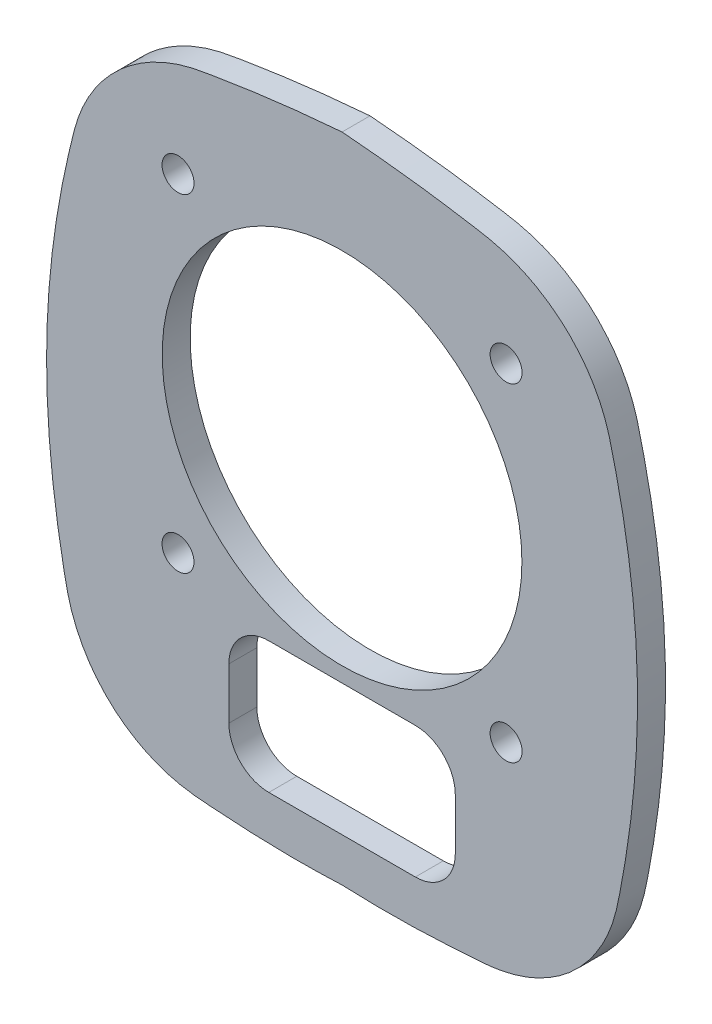
SolidWorks part; units mm, degrees
material "Фанера"
ref_plane "Front Plane" through (0, 0, 0) normal (0, 0, 1) x (1, 0, 0)
ref_plane "Top Plane" through (0, 0, 0) normal (0, 1, 0) x (1, 0, 0)
ref_plane "Right Plane" through (0, 0, 0) normal (1, 0, 0) x (0, 0, -1)
sketch "Эскиз1" plane through (0, 0, 0) normal (0, 0, 1) x (1, 0, 0)
  line L0 (-25.2911, 103.6369) -> (38.3998, 103.6369) construction
  line L1 (0.0004, 137.8459) -> (0.0004, 83.3564) construction
  line L2 (-16.3355, 87.3015) -> (50.6654, 154.3023) construction
  line L4 (-7.3309, 71.0024) -> (7.3317, 71.0024)
  line L5 (-11.3309, 75.0024) -> (-11.3309, 80.1435)
  line L6 (-7.3309, 84.1435) -> (7.3317, 84.1435)
  line L7 (11.3317, 75.0024) -> (11.3317, 80.1435)
  line L8 (-11.3309, 71.0024) -> (11.3317, 84.1435) construction
  line L9 (-11.3309, 84.1435) -> (11.3317, 71.0024) construction
  circle A0 centre (16.4175, 120.0545) radius 1.6
  circle A1 centre (0, 103.6369) radius 5.3081 construction
  circle A2 centre (0, 103.6369) radius 18
  circle A3 centre (-16.4168, 120.0545) radius 1.6
  circle A4 centre (-16.4168, 87.2194) radius 1.6
  circle A5 centre (16.4175, 87.2194) radius 1.6
  arc A6 (7.3317, 84.1435) -> (11.3317, 80.1435) centre (7.3317, 80.1435) cw
  arc A7 (-11.3309, 80.1435) -> (-7.3309, 84.1435) centre (-7.3309, 80.1435) cw
  arc A8 (7.3317, 71.0024) -> (11.3317, 75.0024) centre (7.3317, 75.0024) ccw
  arc A9 (-7.3309, 71.0024) -> (-11.3309, 75.0024) centre (-7.3309, 75.0024) cw
  spline S2 degree 3 poles (0, 131.1062) (-0.3702, 131.0763) (-1.1028, 131.0172) (-2.1891, 130.9196) (-3.4436, 130.7985) (-4.8817, 130.6463) (-6.503, 130.4563) (-8.125, 130.2474) (-9.7417, 130.0206) (-11.3628, 129.775) (-12.676, 129.562) (-13.6897, 129.3901) (-14.4132, 129.2646) (-15.1596, 129.0944) (-15.9282, 128.8804) (-16.7152, 128.6164) (-17.5163, 128.2986) (-18.3267, 127.9229) (-19.728, 127.1697) (-21.748, 125.7276) (-23.5677, 123.7) (-24.6127, 122.0113) (-25.1013, 121.049) (-25.4626, 120.2251) (-25.7389, 119.4608) (-25.9468, 118.7675) (-26.0817, 118.2397) (-26.2129, 117.7174) (-26.5508, 116.3391) (-27.0624, 114.0664) (-27.6532, 110.9226) (-28.1312, 107.7137) (-28.4753, 104.5458) (-28.6991, 101.2935) (-28.8206, 96.9974) (-28.6815, 92.7434) (-28.3105, 88.4657) (-28.0114, 86.0398) (-27.6872, 83.8215) (-27.4469, 82.3517) (-27.1704, 80.8223) (-26.9644, 79.7639) (-26.7959, 78.9056) (-26.6398, 78.2276) (-26.4962, 77.7067) (-26.3157, 77.1264) (-26.0804, 76.4742) (-25.653, 75.4713) (-25.0212, 74.2848) (-23.7978, 72.5158) (-22.2749, 70.9806) (-20.5079, 69.748) (-19.0733, 68.9835) (-17.5657, 68.3965) (-16.3741, 68.0858) (-15.5407, 67.9319) (-15.0588, 67.8587) (-14.5432, 67.7975) (-13.9938, 67.7521) (-13.4123, 67.7047) (-12.6889, 67.6502) (-11.8043, 67.5891) (-10.7388, 67.5241) (-8.9321, 67.4292) (-6.9506, 67.36) (-4.8154, 67.3354) (-3.1864, 67.3427) (-1.5776, 67.3747) (-0.5086, 67.4211) (0, 67.4432) knots 0 0 0 0 0.010771 0.021313 0.031628 0.047323 0.06325 0.078966 0.094746 0.110593 0.126514 0.133325 0.14041 0.147806 0.155515 0.163537 0.171867 0.180498 0.189424 0.217986 0.251993 0.267593 0.275472 0.283275 0.293668 0.299019 0.30426 0.309463 0.314637 0.345412 0.377007 0.407382 0.439473 0.469388 0.501899 0.564079 0.59267 0.626404 0.634941 0.657685 0.669589 0.680012 0.688953 0.694954 0.700182 0.70462 0.712574 0.720276 0.736225 0.751452 0.782552 0.798228 0.813816 0.829575 0.845041 0.849441 0.854152 0.859171 0.864496 0.870136 0.876092 0.885532 0.895852 0.907048 0.937998 0.953339 0.968971 0.985238 1 1 1 1 construction
  spline S3 degree 3 poles (0, 67.4432) (0.2498, 67.4316) (0.7627, 67.4079) (1.5522, 67.3807) (2.3816, 67.3592) (3.4924, 67.3408) (4.8609, 67.3356) (7.0177, 67.3614) (9.2063, 67.4395) (11.3606, 67.5592) (12.7428, 67.6525) (13.8286, 67.7384) (14.6702, 67.8067) (15.4337, 67.9108) (16.4372, 68.0976) (17.7023, 68.4416) (19.1991, 69.0422) (20.6198, 69.8178) (22.3705, 71.0635) (23.8791, 72.6123) (25.088, 74.3955) (25.7081, 75.5866) (26.1255, 76.5907) (26.3812, 77.3194) (26.6103, 78.0983) (26.7713, 78.7963) (26.904, 79.4609) (27.0194, 80.041) (27.1412, 80.6774) (27.2695, 81.37) (27.4848, 82.582) (27.6985, 83.8954) (28.021, 86.1095) (28.3221, 88.5758) (28.6884, 92.8624) (28.8217, 97.1322) (28.6919, 101.4443) (28.4611, 104.7035) (28.1104, 107.8744) (27.6255, 111.0861) (27.0271, 114.2367) (26.4904, 116.6008) (26.103, 118.158) (25.9212, 118.8668) (25.6776, 119.6395) (25.1101, 121.1479) (23.8327, 123.4328) (21.623, 125.8387) (19.5853, 127.2596) (18.1767, 127.9969) (17.3651, 128.3626) (16.5634, 128.671) (15.7765, 128.926) (15.0085, 129.1319) (14.2626, 129.2936) (13.5403, 129.415) (12.5345, 129.5857) (11.2349, 129.7948) (9.1036, 130.1162) (6.9662, 130.4026) (4.8289, 130.6521) (3.2288, 130.8207) (1.6218, 130.9738) (0.5464, 131.0616) (0, 131.1062) knots 0 0 0 0 0.007253 0.014889 0.022909 0.031315 0.04711 0.062594 0.093869 0.110611 0.125167 0.134046 0.142201 0.149649 0.156381 0.171796 0.187581 0.203049 0.218623 0.249784 0.265042 0.281007 0.288624 0.296566 0.303391 0.312159 0.31733 0.323048 0.329311 0.33612 0.343475 0.365012 0.374709 0.408363 0.437047 0.499467 0.532106 0.562131 0.594201 0.6246 0.656308 0.687188 0.69489 0.702849 0.708403 0.718376 0.749562 0.783616 0.812211 0.821107 0.82971 0.838012 0.846006 0.85369 0.861061 0.868129 0.874931 0.890648 0.906302 0.937441 0.953185 0.968707 0.984102 1 1 1 1 construction
  spline S4 degree 1 poles (0.0004, 131.9089) (-0.0011, 66.6424) knots 0 0 1 1 construction
  spline S5 degree 1 poles (-0.0011, 66.6424) (0.0004, 131.9089) knots 0 0 1 1 construction
  spline S6 degree 3 poles (0.0004, 131.9089) (-2.1591, 131.7346) (-5.3932, 131.4185) (-9.6929, 130.8482) (-12.3658, 130.4183) (-14.508, 130.0793) (-16.7336, 129.5269) (-19.3432, 128.4151) (-22.1553, 126.4452) (-24.4752, 123.8994) (-25.8878, 121.4202) (-26.6662, 119.256) (-27.1828, 117.1196) (-27.7959, 114.4843) (-28.4047, 111.2734) (-28.8952, 108.0459) (-29.3767, 103.717) (-29.6542, 98.2761) (-29.4905, 92.8306) (-29.1184, 88.4954) (-28.7207, 85.2562) (-28.3032, 82.5756) (-27.909, 80.4309) (-27.6123, 78.849) (-27.207, 77.1816) (-26.3998, 75.0513) (-24.9514, 72.5746) (-22.5477, 70.0835) (-19.6247, 68.246) (-16.9139, 67.3239) (-14.6389, 66.9838) (-12.4813, 66.8357) (-9.773, 66.6563) (-6.5186, 66.5443) (-3.2584, 66.5254) (-1.0865, 66.5953) (-0.0011, 66.6424) knots -0.000628 -0.000628 -0.000628 -0.000628 0.06189 0.093149 0.124407 0.140037 0.155666 0.186925 0.218184 0.249442 0.280701 0.296331 0.31196 0.343219 0.374478 0.405736 0.436995 0.499513 0.56203 0.593289 0.624548 0.655807 0.671436 0.687065 0.702695 0.718324 0.749583 0.780842 0.812101 0.843359 0.858989 0.874618 0.905877 0.937136 0.968394 0.999653 0.999653 0.999653 0.999653
  spline S7 degree 3 poles (-0.0011, 66.6424) (2.1695, 66.5419) (5.4339, 66.5053) (9.772, 66.6566) (12.4817, 66.8357) (14.6377, 66.9839) (16.9129, 67.3235) (19.6236, 68.2456) (22.5465, 70.0825) (24.9503, 72.573) (26.399, 75.0504) (27.2066, 77.1787) (27.611, 78.8488) (27.9094, 80.43) (28.3025, 82.573) (28.7205, 85.2543) (29.1182, 88.4931) (29.4904, 92.8281) (29.6543, 98.2733) (29.3769, 103.7139) (28.8956, 108.0425) (28.4053, 111.2701) (27.7968, 114.4803) (27.1835, 117.1167) (26.6676, 119.2508) (25.8901, 121.4161) (24.4735, 123.9025) (22.1547, 126.4453) (19.3425, 128.4158) (16.7315, 129.5274) (14.5094, 130.0792) (12.3645, 130.4186) (9.6926, 130.8481) (5.3927, 131.4191) (2.1594, 131.7325) (0.0004, 131.9089) knots 0.000347 0.000347 0.000347 0.000347 0.062864 0.094123 0.125382 0.141011 0.156641 0.187899 0.219158 0.250417 0.281676 0.297305 0.312935 0.328564 0.344193 0.375452 0.406711 0.43797 0.500487 0.563005 0.594264 0.625522 0.656781 0.68804 0.703669 0.719299 0.750558 0.781816 0.813075 0.844334 0.859963 0.875593 0.906852 0.93811 1.000628 1.000628 1.000628 1.000628
  point P21 (0.0004, 77.5729)
  dimension "D2" = 36
  dimension "D4" = 3.2
  dimension "D5" = 4
  dimension "D3" = 45
  dimension "D1" = 0.8
extrude "Бобышка-Вытянуть1" add sketch "Эскиз1" along normal mid plane 2.8
